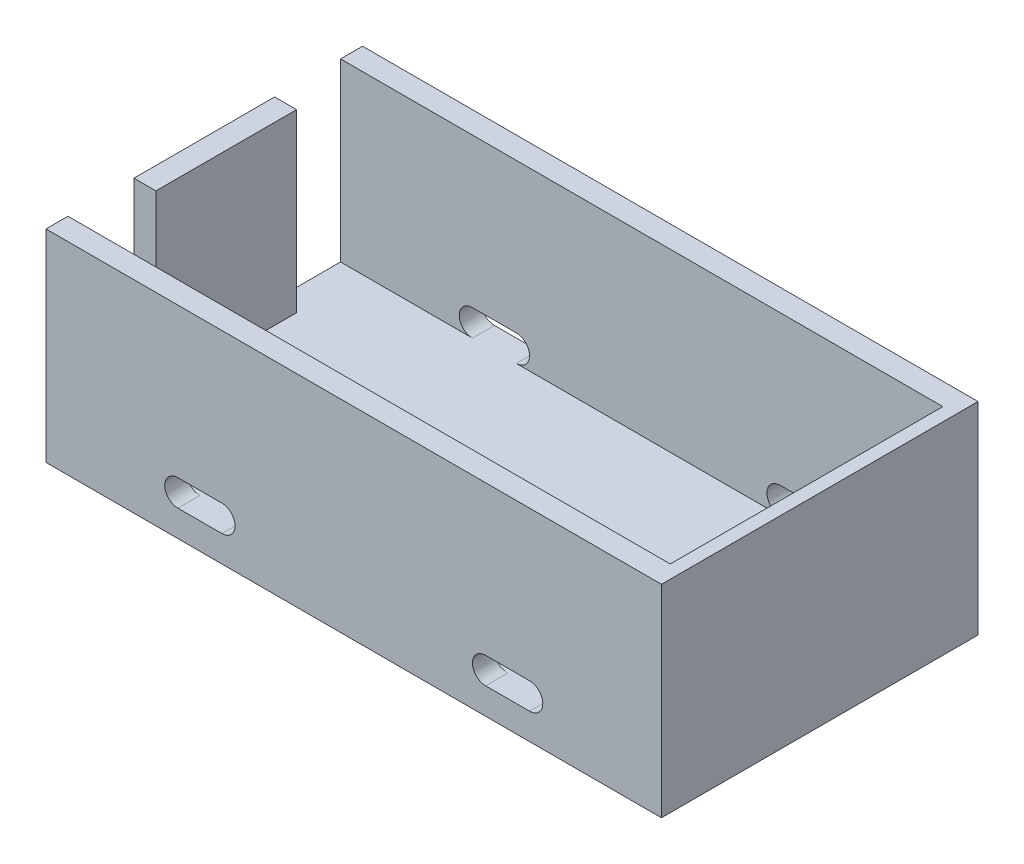
SolidWorks part; units mm, degrees
material "ABS"
ref_plane "Front Plane" through (0, 0, 0) normal (0, 0, 1) x (1, 0, 0)
ref_plane "Top Plane" through (0, 0, 0) normal (0, 1, 0) x (1, 0, 0)
ref_plane "Right Plane" through (0, 0, 0) normal (1, 0, 0) x (0, 0, -1)
sketch "Sketch1" plane through (0, 0, 0) normal (0, 1, 0) x (1, 0, 0)
  line L0 (70, 18) -> (-18.1458, 18) construction
  line L1 (0, 0) -> (70, 0)
  line L2 (0, 0) -> (0, 2.5)
  line L3 (0, 36) -> (70, 36)
  line L4 (70, 0) -> (70, 36)
  line L5 (0, 36) -> (70, 36)
  line L6 (0, 36) -> (0, 33.5)
  line L7 (0, 33.5) -> (70, 33.5)
  line L8 (70, 36) -> (70, 33.5)
  line L9 (35, 36) -> (35, -5.7137) construction
  line L10 (70, 0) -> (70, 2.5)
  line L11 (0, 2.5) -> (70, 2.5)
  line L12 (0, 0) -> (0, 2.5)
  line L13 (0, 0) -> (70, 0)
  line L14 (0, 0) -> (70, 0)
  line L15 (0, 10) -> (0, 26)
  line L16 (68.5, 33.5) -> (70, 33.5)
  line L17 (68.5, 33.5) -> (68.5, 2.5)
  line L18 (68.5, 2.5) -> (70, 2.5)
  line L19 (70, 33.5) -> (70, 2.5)
  line L20 (0, 26) -> (2.5, 26)
  line L21 (0, 26) -> (0, 10)
  line L22 (0, 10) -> (2.5, 10)
  line L23 (2.5, 26) -> (2.5, 10)
  line L24 (0, 33.5) -> (0, 36)
  line L26 (0, 0) -> (70, 0)
  line L27 (0, 0) -> (0, 2.5)
  line L28 (0, 2.5) -> (70, 2.5)
  line L29 (70, 0) -> (70, 2.5)
  dimension "D1" = 70
  dimension "D2" = 36
  dimension "D3" = 2.5
  dimension "D4" = 1.5
  dimension "D5" = 2.5
  dimension "D6" = 7.5
  dimension "D7" = 7.5
extrude "Boss-Extrude1" add sketch "Sketch1" along normal blind 20 contours L27 L26 L29 L28 | L17 L16 L19 L18 | L6 L5 L8 L7 | L21 L20 L23 L22
sketch "Sketch2" plane through (0, 0, 0) normal (0, -1, 0) x (1, 0, 0)
  line L1 (70, 0) -> (0, 0)
  line L2 (70, 0) -> (70, -36)
  line L3 (70, -36) -> (0, -36)
  line L4 (0, 0) -> (0, -36)
extrude "Boss-Extrude2" add sketch "Sketch2" along normal blind 3
sketch "Sketch3" plane through (0, 0, 0) normal (0, 0, 1) x (1, 0, 0)
  line L0 (70, -3) -> (70, 20) construction
  line L1 (0, -3) -> (70, -3)
  line L2 (0, -3) -> (0, 0)
  line L3 (0, 0) -> (70, 0)
  line L4 (70, -3) -> (70, 0)
  line L5 (15, 1.5) -> (20, 1.5) construction
  line L6 (15, 3) -> (20, 3)
  line L7 (15, 0) -> (20, 0)
  line L8 (0, -3) -> (0, 20) construction
  line L9 (35, -3) -> (35, 29.0876) construction
  line L10 (55, 1.5) -> (50, 1.5) construction
  line L11 (55, 3) -> (50, 3)
  line L12 (55, 0) -> (50, 0)
  arc A0 (15, 3) -> (15, 0) centre (15, 1.5) ccw
  arc A1 (20, 0) -> (20, 3) centre (20, 1.5) ccw
  arc A2 (55, 3) -> (55, 0) centre (55, 1.5) cw
  arc A3 (50, 0) -> (50, 3) centre (50, 1.5) cw
  point P9 (17.5, 1.5)
  point P20 (52.5, 1.5)
  dimension "D2" = 1.5
  dimension "D1" = 3
  dimension "D3" = 1.5
  dimension "D4" = 5
  dimension "D5" = 15
extrude "Cut-Extrude1" cut sketch "Sketch3" against normal through all both and the other way through all contours L7 A1 L6 A0 | L11 A3 L12 A2
